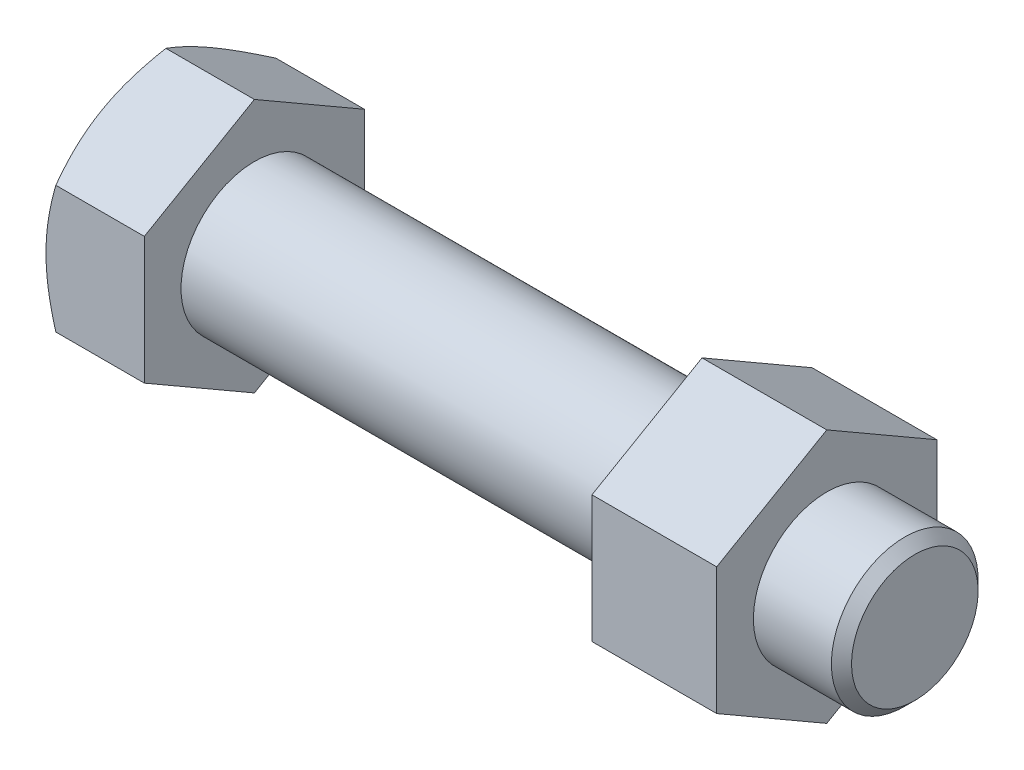
SolidWorks part; units mm, degrees
extrude "BaseHead" add sketch "Sketch1" along normal blind 13.4
sketch "Sketch1" plane through (0, 0, 0) normal (1, 0, 0) x (0, 0, -1)
  line L0 (15, 8.6603) -> (15, -8.6603)
  line L1 (-15, 8.6603) -> (-15, -8.6603)
  line L2 (15, -8.6603) -> (0, -17.3205)
  line L3 (0, -17.3205) -> (-15, -8.6603)
  line L4 (15, 8.6603) -> (0, 17.3205)
  line L5 (0, 17.3205) -> (-15, 8.6603)
  dimension "Width_flats" = 30
  dimension "D2" = 120
  dimension "D3" = 15
  dimension "D4" = 15
  dimension "D5" = 15
material "AISI 304"
ref_plane "Plane1" through (0, 0, 0) normal (0, 0, 1) x (1, 0, 0)
ref_plane "Plane2" through (0, 0, 0) normal (0, 1, 0) x (1, 0, 0)
ref_plane "Plane3" through (0, 0, 0) normal (1, 0, 0) x (0, 0, -1)
sketch "BodySke" plane through (0, 0, 0) normal (0, 0, 1) x (1, 0, 0)
  line L0 (0, 8.6603) -> (0, -8.6603) construction
  line L1 (0, 0) -> (103.4, 0)
  line L2 (0, 0) -> (0, 10)
  line L3 (0, 10) -> (102.026, 10)
  line L4 (103.4, 0) -> (103.4, 8.626)
  line L5 (13.4, 17.3205) -> (13.4, 8.6603) construction
  line L6 (103.4, 8.626) -> (102.026, 10)
  line L7 (0, 0) -> (96.52, 0) construction
  line L8 (103.4, -8.626) -> (102.026, -10) construction
  line L9 (0, -10) -> (102.026, -10) construction
  line L10 (15.9, 15.24) -> (15.9, -1.27) construction
  line L11 (57.4, 15.24) -> (57.4, -1.27) construction
  line L12 (13.4, 8.6603) -> (13.4, -8.6603) construction
  dimension "Diameter" = 20
revolve "BaseBody" add sketch "BodySke"
cosmetic thread "ThreadCosmetic" [suppressed]
fillet "HeadFillet" [suppressed] radius 0.8
sketch "Sketch3" plane through (0, 0, 0) normal (0, 0, 1) x (1, 0, 0)
  line L0 (0, 15) -> (4.2265, 22.3205)
  line L1 (0, 17.3205) -> (0, 8.6603) construction
  line L2 (4.2265, 22.3205) -> (4.2265, 27.3205)
  line L3 (4.2265, 27.3205) -> (-10, 27.3205)
  line L4 (-10, 27.3205) -> (-10, 15)
  line L5 (-10, 15) -> (0, 15)
  line L6 (0, 0) -> (99.06, 0) construction
  line L7 (13.4, 17.3205) -> (0, 17.3205) construction
  dimension "D1" = 15
  dimension "D2" = 5
  dimension "D3" = 10
  dimension "D4" = 5
  dimension "Head_ch_ang" = 30
revolve "HeadChamfer" cut sketch "Sketch3" angle 360 about L6
sketch "ThdSchSke" plane through (0, 0, 0) normal (0, 0, 1) x (1, 0, 0)
  line L0 (57.4, -8.626) -> (56.4379, -10)
  line L1 (57.4, -8.626) -> (58.3621, -10)
  line L2 (58.3621, -10) -> (58.3621, -12.5)
  line L3 (-3.175, 0) -> (5.1513, 0) construction
  line L5 (58.3621, -12.5) -> (56.4379, -12.5)
  line L6 (56.4379, -12.5) -> (56.4379, -10)
  dimension "Thread_minor" = 17.252
  dimension "Diameter" = 20
  dimension "Start" = 57.4
revolve "ThreadSchematic" [suppressed] cut sketch "ThdSchSke" angle 360 about L3
pattern_linear "ThdSchPat" [suppressed]
ref_plane "Plane4" through (74.4, 0, 0) normal (1, 0, 0) x (0, 0, -1)
sketch "Sketch4" plane through (74.4, 0, 0) normal (1, 0, 0) x (0, 0, -1)
  line L1 (0, 17.3205) -> (-15, 8.6603)
  line L2 (-15, 8.6603) -> (-15, -8.6603)
  line L3 (-15, -8.6603) -> (0, -17.3205)
  line L4 (0, -17.3205) -> (15, -8.6603)
  line L5 (15, -8.6603) -> (15, 8.6603)
  line L6 (15, 8.6603) -> (0, 17.3205)
  circle A0 centre (0, 0) radius 15 construction
extrude "Boss-Extrude1" add sketch "Sketch4" along normal blind 17
equation "\"D3@Sketch1\" = \"Width_flats@Sketch1\" / 2"
equation "\"D4@Sketch1\" = \"D3@Sketch1\""
equation "\"D5@Sketch1\" = \"D4@Sketch1\""
equation "\"Thread_minor@ThreadCosmetic\" = \"Minor_dia@BodySke\""
equation "\"D1@Sketch3\" = \"Width_flats@Sketch1\" / 2"
equation "' \"D1@Sketch4\" = \"Width_flats@Sketch1\""
equation "\"Thread_length@ThreadCosmetic\" = ((sgn( (\"Length@BodySke\" - \"Advance@BodySke\" ) - \"Thread_nom@BodySke\" )-1)*( (\"Length@BodySke\" - \"Advance@BodySke\" ) - \"Thread_nom@BodySke\" ))/-2+ \"Thread_nom@BodySke\""
equation "\"Thread_minor@ThdSchSke\" = \"Minor_dia@BodySke\""
equation "\"Diameter@ThdSchSke\" = \"Diameter@BodySke\""
equation "\"Overcut@ThdSchSke\" = \"Diameter@BodySke\" * 1.25"
equation "\"Start@ThdSchSke\" = \"Head_ht@BaseHead\" + \"Length@BodySke\" - \"Thread_length@ThreadCosmetic\"  '---Non-countersunk---"
equation "\"Num_threads@ThdSchPat\" = int( \"Thread_length@ThreadCosmetic\" / \"Advance@BodySke\" + 0.999 )  + 1"
equation "\"Advance@ThdSchPat\" = \"Thread_length@ThreadCosmetic\" /  (\"Num_threads@ThdSchPat\" - 1) 'relax it"
equation "\"Num_threads@ThdSchPat\" = \"Num_threads@ThdSchPat\" - sgn( \"Num_threads@ThdSchPat\" - 1) '---chamfered tips only---"
